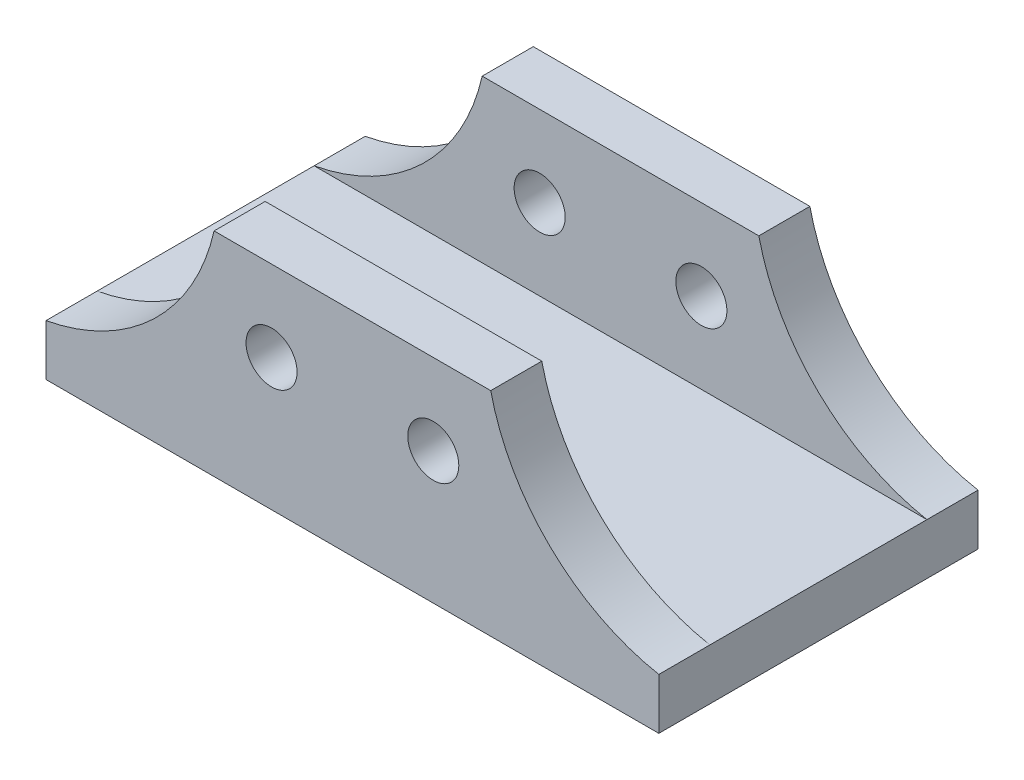
SolidWorks part; units mm, degrees
ref_plane "Front Plane" through (0, 0, 0) normal (0, 0, 1) x (1, 0, 0)
ref_plane "Top Plane" through (0, 0, 0) normal (0, 1, 0) x (1, 0, 0)
ref_plane "Right Plane" through (0, 0, 0) normal (1, 0, 0) x (0, 0, -1)
sketch "Sketch1" plane through (0, 0, 0) normal (0, 0, 1) x (1, 0, 0)
  line L0 (-72, -25.5) -> (72, -25.5)
  line L1 (-72, -37.5) -> (72, -37.5)
  line L2 (-72, -25.5) -> (-72, -37.5)
  line L3 (-32.5, 12.5) -> (32.5, 12.5)
  line L4 (72, -25.5) -> (72, -37.5)
  line L5 (0, 66.14) -> (0, -66.14) construction
  arc A0 (32.5, 12.5) -> (72, -25.5) centre (81.2436, 23.6381) ccw
  arc A1 (-32.5, 12.5) -> (-72, -25.5) centre (-81.2436, 23.6381) cw
  circle A2 centre (19, -6.5) radius 6
  circle A3 centre (-19, -6.5) radius 6
  point P0 (0, 0)
  point P12 (0, 12.5)
  point P15 (0, 0)
  dimension "D2" = 50
  dimension "D6" = 37.5
  dimension "D9" = 50
  dimension "D10" = 12
  dimension "D1" = 144
  dimension "D4" = 65
  dimension "D5" = 50
  dimension "D7" = 49.1381
  dimension "D8" = 81.2436
  dimension "D11" = 19
  dimension "D12" = 53
  dimension "D3" = 12
extrude "Boss-Extrude1" add sketch "Sketch1" along normal mid plane 75 contours L5 L3 A1 L0 A3 | L3 L5 L0 A0 A2 | L5 L0 L2 L1 | L0 L5 L1 L4
sketch "Sketch2" plane through (0, 12.5, 0) normal (0, 1, 0) x (1, 0, 0)
  line L0 (72, 37.5) -> (32.5, 37.5) construction
  line L1 (-82.1947, 25.5) -> (82.1947, 25.5)
  line L2 (-82.1947, 25.5) -> (-82.1947, -25.5)
  line L3 (-82.1947, -25.5) -> (82.1947, -25.5)
  line L4 (82.1947, 25.5) -> (82.1947, -25.5)
  line L5 (32.5, -37.5) -> (72, -37.5) construction
  dimension "D1" = 12
  dimension "D2" = 12
extrude "Cut-Extrude1" cut sketch "Sketch2" against normal blind 38
sketch "Sketch3" plane through (0, -25.5, 0) normal (0, 1, 0) x (1, 0, 0)
  circle A0 centre (0, 0) radius 5
  dimension "D1" = 10
extrude "Cut-Extrude2" cut sketch "Sketch3" against normal through all
